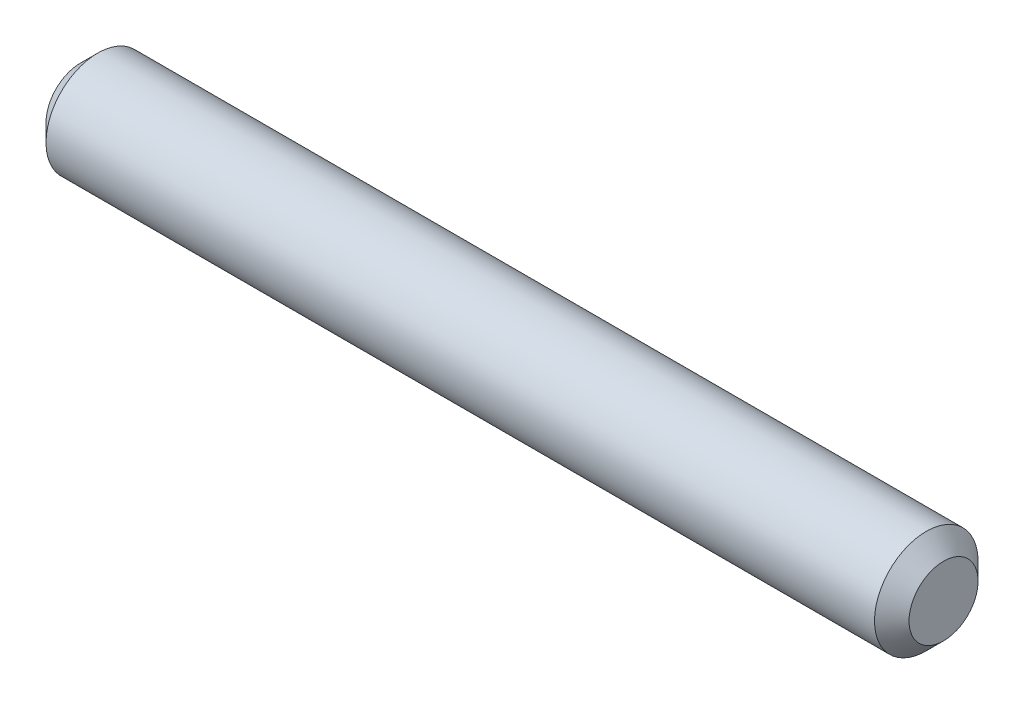
SolidWorks part; units mm, degrees
ref_plane "Front" through (0, 0, 0) normal (0, 0, 1) x (1, 0, 0)
ref_plane "Top" through (0, 0, 0) normal (0, 1, 0) x (1, 0, 0)
ref_plane "Right" through (0, 0, 0) normal (1, 0, 0) x (0, 0, -1)
sketch "Sketch1" plane through (0, 0, 0) normal (0, 0, 1) x (1, 0, 0)
  line L0 (0, 0) -> (33, 0) construction
  line L1 (4, 0) -> (4, 1)
  line L2 (4, 1) -> (4.5, 1.5)
  line L3 (4.5, 1.5) -> (28.5, 1.5)
  line L4 (28.5, 1.5) -> (29, 1)
  line L5 (29, 1) -> (29, 0)
  line L6 (29, 0) -> (4, 0)
  point P15 (16.5, 0)
  point P16 (16.5, 0)
  dimension "D1" = 0.5
  dimension "D2" = 25
  dimension "D3" = 0.5
  dimension "D4" = 1.5
  dimension "D5" = 33
revolve "Revolve1" add sketch "Sketch1" angle 360 about L0
